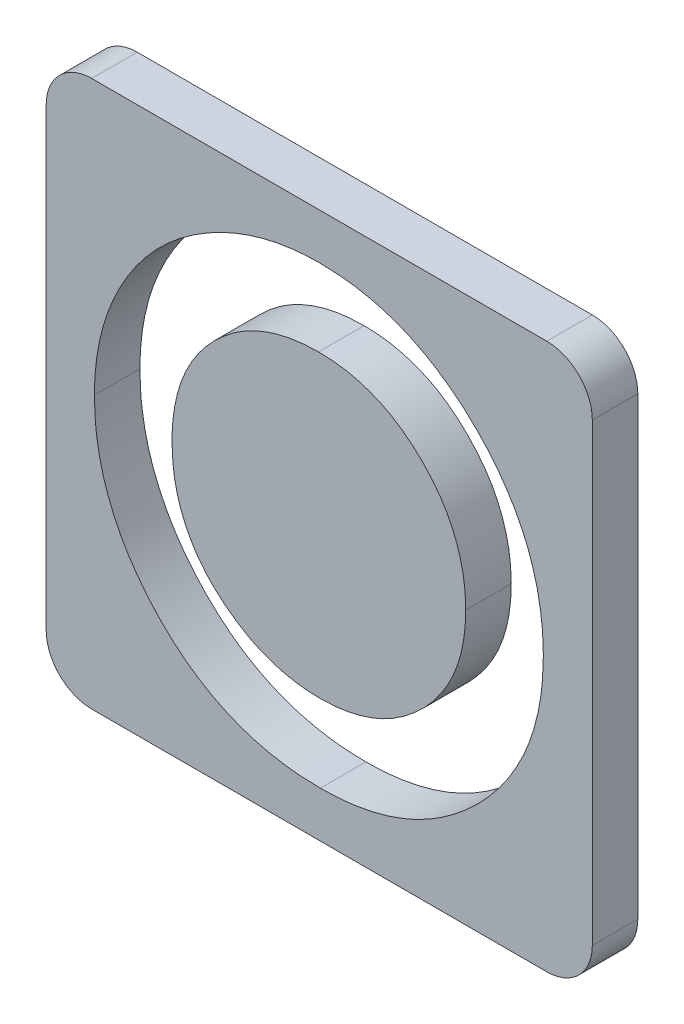
SolidWorks part; units mm, degrees
ref_plane "Front Plane" through (0, 0, 0) normal (0, 0, 1) x (1, 0, 0)
ref_plane "Top Plane" through (0, 0, 0) normal (0, 1, 0) x (1, 0, 0)
ref_plane "Right Plane" through (0, 0, 0) normal (1, 0, 0) x (0, 0, -1)
sketch "Sketch1" plane through (0, 0, 0) normal (0, 0, 1) x (1, 0, 0)
  line L1 (-50, 60) -> (50, 60)
  line L2 (-60, 50) -> (-60, -50)
  line L3 (-50, -60) -> (50, -60)
  line L4 (60, 50) -> (60, -50)
  line L5 (-60, 60) -> (60, -60) construction
  line L6 (-60, -60) -> (60, 60) construction
  arc A0 (-60, -50) -> (-50, -60) centre (-50, -50) ccw
  arc A1 (50, -60) -> (60, -50) centre (50, -50) ccw
  arc A2 (50, 60) -> (60, 50) centre (50, 50) cw
  arc A3 (-50, 60) -> (-60, 50) centre (-50, 50) ccw
  point P0 (0, 0)
  dimension "D3" = 10
  dimension "D1" = 120
  dimension "D2" = 120
extrude "Boss-Extrude1" add sketch "Sketch1" along normal blind 10 contours A3 L2 A0 L3 A1 L4 A2 L1
sketch "Sketch2" plane through (0, 0, 10) normal (0, 0, 1) x (1, 0, 0)
  line L0 (0, 0) -> (0, 40) construction
  line L1 (-50, 50) -> (50, 50) construction
  line L2 (-50, 50) -> (-50, -50) construction
  line L3 (-50, -50) -> (50, -50) construction
  line L4 (50, 50) -> (50, -50) construction
  line L5 (-50, 50) -> (50, -50) construction
  line L6 (-50, -50) -> (50, 50) construction
  line L7 (0, 40) -> (-40, 40) construction
  line L8 (-40, 40) -> (-40, 0) construction
  line L9 (-40, 0) -> (0, 0) construction
  line L11 (0, 20) -> (-20, 20) construction
  line L12 (-20, 40) -> (-20, 20) construction
  circle A0 centre (0, 40) radius 4 construction
  circle A1 centre (0, 20) radius 4 construction
  circle A2 centre (0, 0) radius 4 construction
  circle A3 centre (-20, 20) radius 4 construction
  circle A4 centre (-20, 40) radius 4 construction
  circle A5 centre (-40, 40) radius 4 construction
  circle A6 centre (0, 0) radius 4 construction
  circle A7 centre (20, 0) radius 4 construction
  circle A8 centre (40, 0) radius 4 construction
  circle A9 centre (40, 20) radius 4 construction
  circle A10 centre (40, 40) radius 4 construction
  circle A11 centre (20, 20) radius 4 construction
  circle A12 centre (0, 0) radius 4 construction
  circle A13 centre (0, -20) radius 4 construction
  circle A14 centre (0, -40) radius 4 construction
  circle A15 centre (20, -40) radius 4 construction
  circle A16 centre (40, -40) radius 4 construction
  circle A17 centre (20, -20) radius 4 construction
  circle A18 centre (0, 0) radius 4 construction
  circle A19 centre (-20, 0) radius 4 construction
  circle A20 centre (-40, 0) radius 4 construction
  circle A21 centre (-40, -20) radius 4 construction
  circle A22 centre (-40, -40) radius 4 construction
  circle A23 centre (-20, -20) radius 4 construction
  text T0 "O" font "Century Gothic" height 95
  point P0 (0, 0)
  point P55 (0, 0)
  dimension "D4" = 8
  dimension "D1" = 100
  dimension "D2" = 100
  dimension "D3" = 40
  dimension "D5" = 4
extrude "Cut-Extrude28" cut sketch "Sketch2" against normal blind 10
